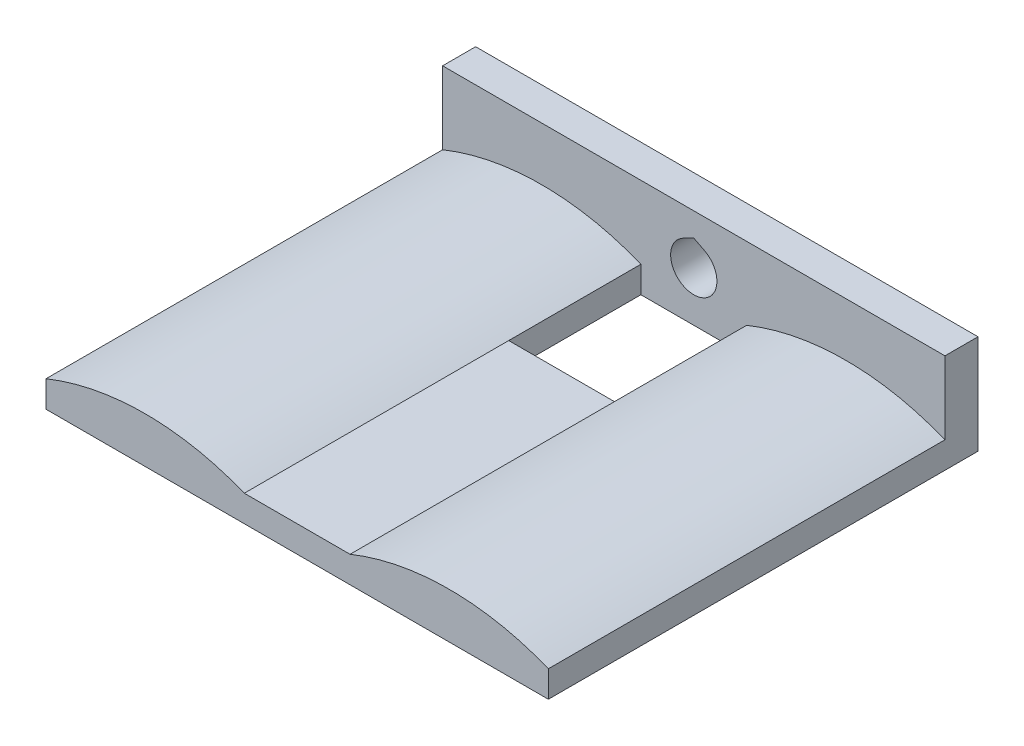
SolidWorks part; units mm, degrees
ref_plane "Frontal Plane" through (0, 0, 0) normal (0, 0, 1) x (1, 0, 0)
ref_plane "Horizontal Plane" through (0, 0, 0) normal (0, 1, 0) x (1, 0, 0)
ref_plane "Profile Plane" through (0, 0, 0) normal (1, 0, 0) x (0, 0, -1)
sketch "Sketch1" plane through (0, 0, 0) normal (0, 0, 1) x (1, 0, 0)
  line L1 (-19, -3.75) -> (19, -3.75)
  line L2 (-19, -3.75) -> (-19, 3.75)
  line L3 (-19, 3.75) -> (19, 3.75)
  line L4 (19, -3.75) -> (19, 3.75)
  line L5 (-19, -3.75) -> (19, 3.75) construction
  line L6 (-19, 3.75) -> (19, -3.75) construction
  line L7 (0, 1.9614) -> (0.7903, 1.5614)
  line L8 (0, 1.9614) -> (-0.7903, 1.5614)
  arc A0 (-0.7903, 1.5614) -> (0.7903, 1.5614) centre (0, 0) ccw
  point P0 (0, 0)
  point P7 (0, 1.2794)
  point P8 (0, 1.8253)
  point P10 (-0.5586, 1.6585)
  point P13 (0, 1.9407)
  dimension "D1" = 3.5
  dimension "D2" = 38
  dimension "D3" = 7.5
  dimension "D4" = 0.4
extrude "Boss-Extrude1" add sketch "Sketch1" along normal blind 2.5
sketch "Sketch3" plane through (0, 0, 2.5) normal (0, 0, 1) x (1, 0, 0)
  line L0 (-19, -3.75) -> (19, -3.75)
  line L1 (19, -3.75) -> (19, -2.75)
  line L2 (19, -3.75) -> (19, 3.75) construction
  line L3 (-19, -3.75) -> (-19, -2.75)
  line L4 (-19, 3.75) -> (-19, -3.75) construction
  arc A0 (-19, -2.75) -> (19, -2.75) centre (0, -66.0852) cw
  dimension "D1" = 1
extrude "Boss-Extrude4" [suppressed] add sketch "Sketch3" along normal blind 30
sketch "Sketch5" plane through (0, 0, 2.5) normal (0, 0, 1) x (1, 0, 0)
  circle A0 centre (0, 0) radius 3
  dimension "D1" = 6
extrude "Cut-Extrude1" [suppressed] cut sketch "Sketch5" along normal blind 9
sketch "Sketch6" plane through (0, 0, 2.5) normal (0, 0, 1) x (1, 0, 0)
  line L0 (-19, -3.75) -> (-19, -1.75)
  line L1 (-19, 3.75) -> (-19, -3.75) construction
  line L2 (-19, -3.75) -> (-4, -3.75)
  line L3 (-19, -3.75) -> (19, -3.75) construction
  line L4 (-4, -3.75) -> (-4, -1.75)
  arc A0 (-19, -1.75) -> (-4, -1.75) centre (-11.5, -20.2905) cw
  point P10 (0, 0)
  dimension "D3" = 20
  dimension "D1" = 2
  dimension "D2" = 15
extrude "Boss-Extrude5" add sketch "Sketch6" along normal blind 30
mirror "Mirror1" about plane through (0, 0, 0) normal (1, 0, 0) of "Boss-Extrude5"
sketch "Sketch7" plane through (0, 0, 32.5) normal (0, 0, 1) x (1, 0, 0)
  line L0 (-4, -3.75) -> (4, -3.75)
  line L1 (4, -3.75) -> (4, -1.75)
  line L2 (4, -1.75) -> (-4, -1.75)
  line L3 (-4, -1.75) -> (-4, -3.75)
extrude "Boss-Extrude6" add sketch "Sketch7" against normal blind 20
